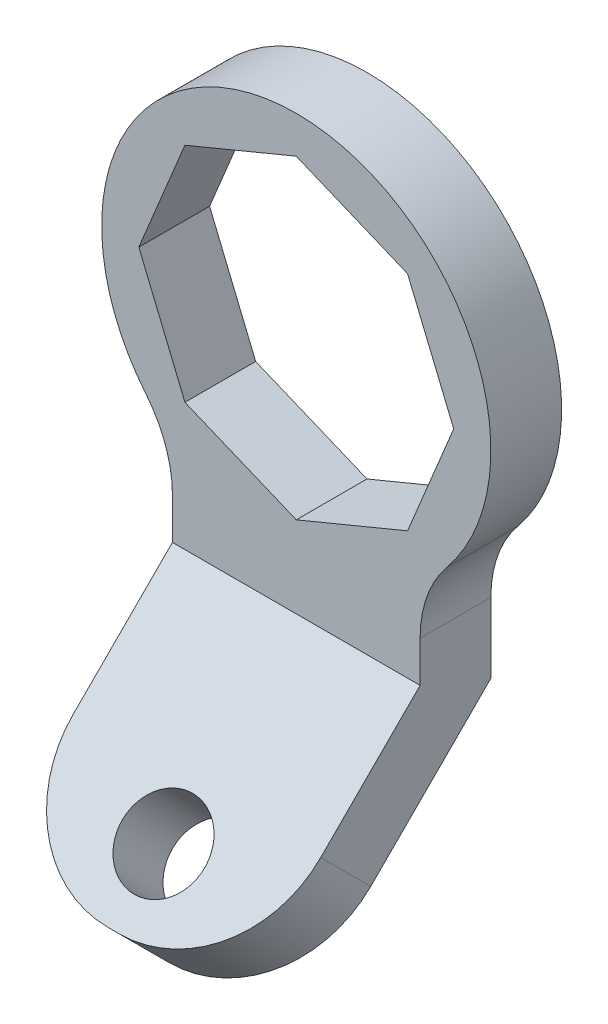
SolidWorks part; units mm, degrees
material "ABS"
ref_plane "前视基准面" through (0, 0, 0) normal (0, 0, 1) x (1, 0, 0)
ref_plane "上视基准面" through (0, 0, 0) normal (0, 1, 0) x (1, 0, 0)
ref_plane "右视基准面" through (0, 0, 0) normal (1, 0, 0) x (0, 0, -1)
sketch "草图1" plane through (0, 0, 0) normal (0, 0, 1) x (1, 0, 0)
  line L0 (13.35, 0) -> (9.4399, -9.4399)
  line L1 (9.4399, -9.4399) -> (0, -13.35)
  line L2 (0, -13.35) -> (-9.4399, -9.4399)
  line L3 (-9.4399, -9.4399) -> (-13.35, 0)
  line L4 (-13.35, 0) -> (-9.4399, 9.4399)
  line L5 (-9.4399, 9.4399) -> (0, 13.35)
  line L6 (0, 13.35) -> (9.4399, 9.4399)
  line L7 (9.4399, 9.4399) -> (13.35, 0)
  circle A0 centre (0, 0) radius 13.35 construction
  circle A1 centre (0, 0) radius 16.5
  dimension "D1" = 26.7
  dimension "D2" = 33
extrude "凸台-拉伸1" add sketch "草图1" along normal blind 6 contours A0 | A1 | L7 L0 L1 L2 L3 L4 L5 L6
sketch "草图2" plane through (0, 0, 6) normal (0, 0, 1) x (1, 0, 0)
  line L1 (-10.5, -30) -> (10.5, -30)
  line L2 (-10.5, -30) -> (-10.5, 3.3)
  line L3 (-10.5, 3.3) -> (10.5, 3.3)
  line L4 (10.5, -30) -> (10.5, 3.3)
  line L5 (-10.5, -30) -> (10.5, 3.3) construction
  line L6 (-10.5, 3.3) -> (10.5, -30) construction
  point P0 (0, -13.35)
  circle M13 centre (0, 0) radius 16.5
  dimension "D1" = 21
  dimension "D2" = 30
extrude "凸台-拉伸2" add sketch "草图2" against normal blind 6 contours L1 L4 L2 M13
sketch "草图3" plane through (10.5, 0, 0) normal (1, 0, 0) x (0, 0, -1)
  line L0 (-6, -20.2574) -> (-21.5, -35.7574)
  line L1 (-6, -30) -> (-6, -12.7279) construction
  line L2 (-21.5, -35.7574) -> (-17.2574, -40)
  line L3 (-17.2574, -40) -> (0, -22.7426)
  line L4 (0, -30) -> (-6, -30) construction
  line L5 (0, -22.7426) -> (-6, -20.2574)
  line L6 (0, -30) -> (0, -12.7279) construction
  line L7 (-6, -30) -> (-15.7426, -30)
  line L8 (-6, -24) -> (-9.7426, -24)
  line L9 (-6, -24) -> (-6, -30)
  line M5 (-6, -12.7279) -> (-6, -30)
  dimension "D1" = 15.5
  dimension "D2" = 6
  dimension "D3" = 45
  dimension "D4" = 10
  dimension "D5" = 6
extrude "凸台-拉伸3" add sketch "草图3" against normal blind 21 contours L8 L0 L7 L3 M5 | L7 L3 M5 | L3 L7 L0 L2
sketch "草图4" plane through (0, -7.1287, -7.1287) normal (0, 0.7071, 0.7071) x (1, 0, 0)
  line L0 (0, -40.4871) -> (0, -18.5668) construction
  line L1 (-10.5, -40.4871) -> (10.5, -40.4871) construction
  line L2 (-10.5, -18.5668) -> (10.5, -18.5668) construction
  circle A0 centre (0, -34.4871) radius 3.5
  dimension "D1" = 7
  dimension "D2" = 6
extrude "切除-拉伸1" cut sketch "草图4" against normal through all
sketch "草图5" plane through (10.5, 0, 0) normal (1, 0, 0) x (0, 0, -1)
  line L0 (-7.2574, -30) -> (0, -22.7426)
  line L1 (0, -30) -> (0, -12.7279) construction
  line M7 (-7.2574, -30) -> (0, -30)
  line M8 (0, -30) -> (0, -12.7279)
  dimension "D1" = 45
extrude "切除-拉伸3" cut sketch "草图5" against normal through all and the other way through all contours L0 M7 M8
sketch "草图6" plane through (10.5, 0, 0) normal (1, 0, 0) x (0, 0, -1)
  line L0 (-9.7426, -24) -> (-6, -20.2574)
  line L1 (-6, -24) -> (-6, -12.7279) construction
  line L9 (-17.2574, -40) -> (0, -22.7426)
  line L10 (0, -22.7426) -> (0, -12.7279)
  line L11 (0, -12.7279) -> (-6, -12.7279)
  line L12 (-6, -12.7279) -> (-6, -24)
  line L13 (-6, -24) -> (-9.7426, -24)
  line L14 (-9.7426, -24) -> (-21.5, -35.7574)
  line L15 (-21.5, -35.7574) -> (-17.2574, -40)
  line L16 (-17.2574, -40) -> (0, -22.7426)
  line L17 (0, -22.7426) -> (0, -12.7279)
  line L18 (0, -12.7279) -> (-6, -12.7279)
  line L19 (-6, -12.7279) -> (-6, -20.2574)
  line L21 (-9.7426, -24) -> (-21.5, -35.7574)
  line L22 (-21.5, -35.7574) -> (-17.2574, -40)
  line M12 (-6, -12.7279) -> (-6, -24)
  line M13 (-6, -24) -> (-9.7426, -24)
  dimension "D1" = 45
  dimension "D2" = 0
extrude "凸台-拉伸4" add sketch "草图6" against normal up to surface (21 mm away) contours L0 M13 M12 up to face at (-10.5, -24.5651, 8.6429)
fillet "圆角3" radius 10 4 edges at (10.5, -37.8787, 19.3787) (-10.5, -37.8787, 19.3787) (10.5, -12.7279, 3) (-10.5, -12.7279, 3)
